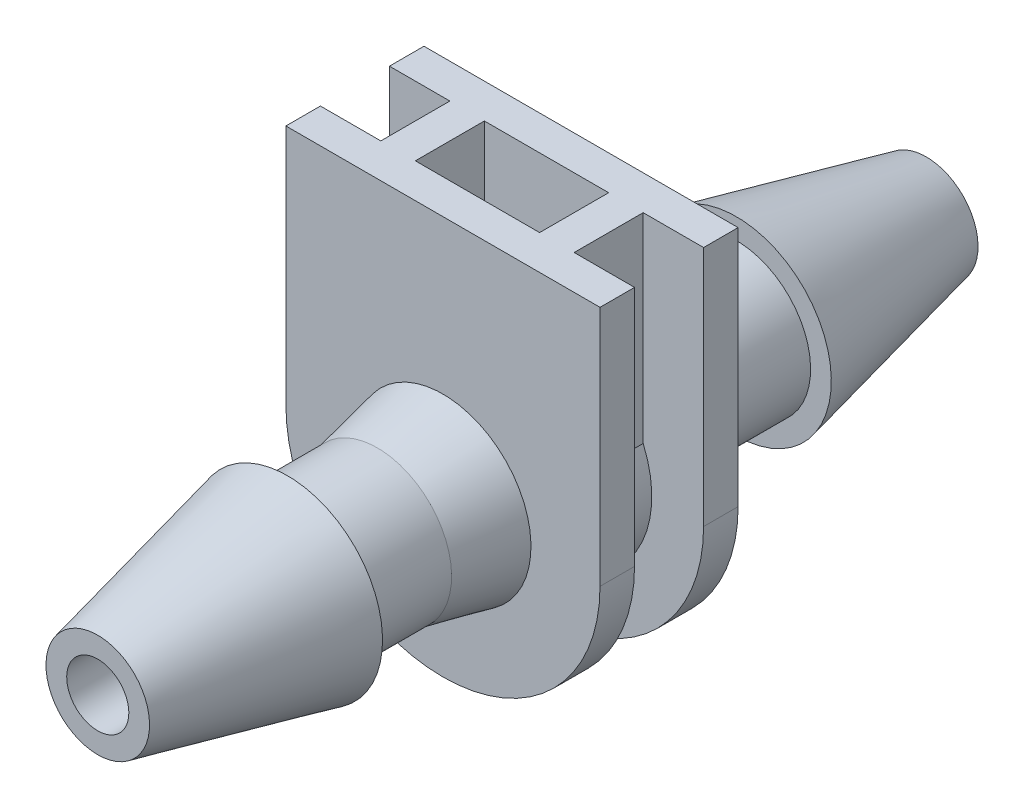
SolidWorks part; units mm, degrees
ref_plane "Front Plane" through (0, 0, 0) normal (0, 0, 1) x (1, 0, 0)
ref_plane "Top Plane" through (0, 0, 0) normal (0, 1, 0) x (1, 0, 0)
ref_plane "Right Plane" through (0, 0, 0) normal (1, 0, 0) x (0, 0, -1)
sketch "Sketch1" plane through (0, 0, 0) normal (1, 0, 0) x (0, 0, -1)
  line L0 (6.5, 2.75) -> (12, 1.5)
  line L1 (-12, 0) -> (12, 0) construction
  line L2 (12, 1.5) -> (12, -1.5) construction
  line L3 (6.5, 2.75) -> (6.5, -2.75) construction
  line L4 (12, 1.5) -> (12, 0.9)
  line L5 (12, 0.9) -> (-12, 0.9)
  line L6 (6.5, 2.75) -> (6.5, 2.15)
  line L7 (6.5, 2.15) -> (3.9, 2.15)
  line L8 (3.9, 2.15) -> (2, 2.55)
  line L9 (6.5, 2.15) -> (6.5, -2.15) construction
  line L10 (2, 2.55) -> (2, -2.55) construction
  line L11 (1, 4.55) -> (2, 4.55)
  line L12 (2, 4.55) -> (2, 2.55)
  line L13 (1, 4.55) -> (1, 3.05)
  line L14 (1, 3.05) -> (-1, 3.05)
  line L15 (0, -1.0893) -> (0, 0.4501) construction
  line L16 (-12, 1.5) -> (-12, 0.9)
  line L17 (-6.5, 2.75) -> (-12, 1.5)
  line L18 (-6.5, 2.75) -> (-6.5, 2.15)
  line L19 (-6.5, 2.15) -> (-3.9, 2.15)
  line L20 (-3.9, 2.15) -> (-2, 2.55)
  line L21 (-2, 4.55) -> (-2, 2.55)
  line L22 (-1, 4.55) -> (-2, 4.55)
  line L23 (-1, 4.55) -> (-1, 3.05)
  point P0 (6.5, 0)
  point P9 (6.5, 0)
  point P14 (0, 0)
  point P16 (2, 0)
  point P22 (0, 0.9)
  point P33 (0, 3.05)
  dimension "D1" = 24
  dimension "D2" = 3
  dimension "D3" = 5.5
  dimension "D4" = 5.5
  dimension "D5" = 0.6
  dimension "D6" = 4.3
  dimension "D7" = 5.1
  dimension "D8" = 4.5
  dimension "D9" = 2.6
  dimension "D10" = 2
  dimension "D11" = 1
  dimension "D12" = 1.5
revolve "Revolve1" add sketch "Sketch1" angle 360 about L1
sketch "Sketch2" plane through (0, 0, 0) normal (0, 1, 0) x (1, 0, 0)
  line L0 (-4.55, 2) -> (-4.55, 1)
  line L1 (-4.55, 1) -> (-2.8, 1)
  line L2 (-3.05, 1) -> (3.05, 1) construction
  line L3 (-2.8, 1) -> (-2.8, -1)
  line L4 (4.55, -1) -> (-4.55, -1) construction
  line L5 (-2.8, -1) -> (-4.55, -1)
  line L6 (-4.55, -1) -> (-4.55, -2)
  line L7 (-4.55, -2) -> (4.55, -2)
  line L8 (4.55, -2) -> (4.55, -1)
  line L9 (4.55, -1) -> (2.8, -1)
  line L10 (2.8, -1) -> (2.8, 1)
  line L11 (2.8, 1) -> (4.55, 1)
  line L12 (-4.55, 1) -> (4.55, 1) construction
  line L13 (4.55, 1) -> (4.55, 2)
  line L14 (4.55, 2) -> (-4.55, 2)
  line L15 (-2.8, 0) -> (2.8, 0) construction
  line L16 (-1.8, 1) -> (-1.8, -1)
  line L17 (-1.8, -1) -> (1.8, -1)
  line L18 (1.8, -1) -> (1.8, 1)
  line L19 (1.8, 1) -> (-1.8, 1)
  line L20 (-1.8, 0) -> (-2.8, 0) construction
  line L21 (2.8, 0) -> (1.8, 0) construction
  point P27 (0, 0)
  dimension "D1" = 1
  dimension "D2" = 3.6
extrude "Boss-Extrude1" add sketch "Sketch2" along normal blind 7
